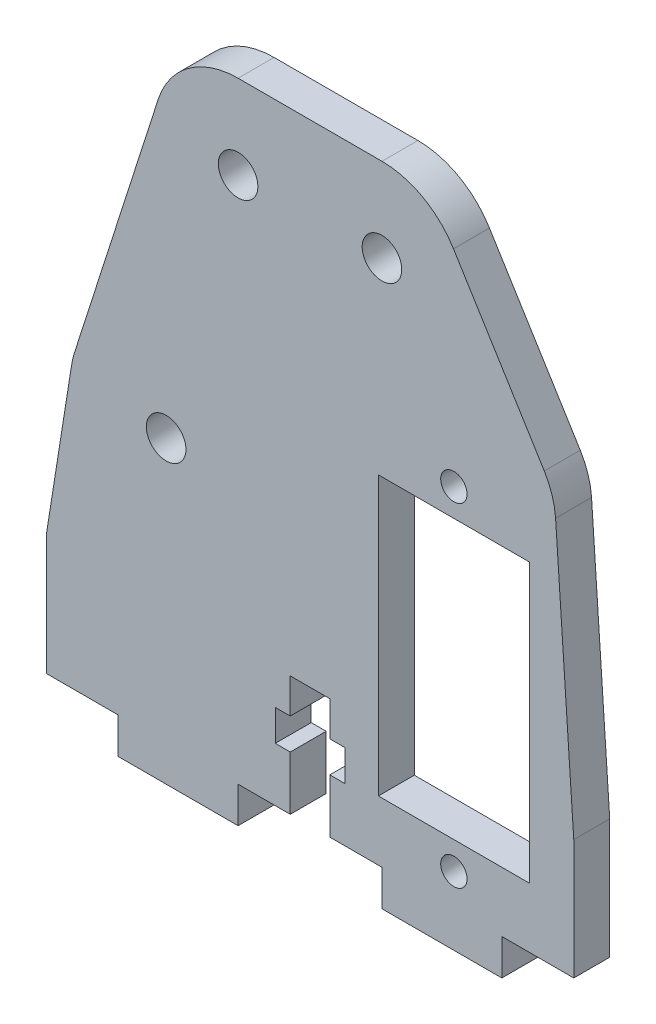
SolidWorks part; units mm, degrees
ref_plane "Спереди" through (0, 0, 0) normal (0, 0, 1) x (1, 0, 0)
ref_plane "Сверху" through (0, 0, 0) normal (0, 1, 0) x (1, 0, 0)
ref_plane "Справа" through (0, 0, 0) normal (1, 0, 0) x (0, 0, -1)
other "Configuration Table"
sketch "Eskiz_kontur" plane through (0, 0, 0) normal (0, 0, 1) x (1, 0, 0)
  line L0 (-19.6085, 2.4721) -> (-12.6574, 24.1631)
  line L1 (-6, 29) -> (6, 29)
  line L2 (-22, -12) -> (-19.9015, 1.2515)
  line L3 (-22, -22) -> (-22, -12)
  line L4 (11.9685, 25.6575) -> (19.5422, 13.3962)
  line L5 (-16, -22) -> (-22, -22)
  line L6 (-16, -25) -> (-16, -22)
  line L7 (20.4842, 10.4534) -> (22, -12)
  line L8 (-6, -25) -> (-16, -25)
  line L9 (22, -12) -> (22, -22)
  line L10 (-6, -22) -> (-6, -25)
  line L11 (22, -22) -> (16, -22)
  line L12 (-1.65, -22) -> (-6, -22)
  line L13 (16, -22) -> (16, -25)
  line L14 (-1.65, -17.5) -> (-1.65, -22)
  line L15 (16, -25) -> (6, -25)
  line L16 (-2.9, -17.5) -> (-1.65, -17.5)
  line L17 (6, -25) -> (6, -22)
  line L18 (-2.9, -14.9) -> (-2.9, -17.5)
  line L19 (6, -22) -> (1.65, -22)
  line L20 (-1.65, -14.9) -> (-2.9, -14.9)
  line L21 (1.65, -22) -> (1.65, -17.5)
  line L22 (-1.65, -12) -> (-1.65, -14.9)
  line L23 (1.65, -17.5) -> (2.9, -17.5)
  line L24 (1.65, -12) -> (-1.65, -12)
  line L25 (2.9, -17.5) -> (2.9, -14.9)
  line L26 (1.65, -14.9) -> (1.65, -12)
  line L27 (2.9, -14.9) -> (1.65, -14.9)
  line L28 (18.3, 6.2) -> (5.7, 6.2)
  line L29 (5.7, 6.2) -> (5.7, -17)
  line L30 (18.3, -17) -> (18.3, 6.2)
  line L31 (5.7, -17) -> (18.3, -17)
  arc A0 (-12.6574, 24.1631) -> (-6, 29) centre (-6, 22) cw
  arc A1 (-19.9015, 1.2515) -> (-19.6085, 2.4721) centre (-11.9999, 0) cw
  arc A2 (6, 29) -> (11.9685, 25.6575) centre (6, 22) cw
  arc A3 (19.5422, 13.3962) -> (20.4842, 10.4534) centre (14, 10) cw
extrude "Plastina" add sketch "Eskiz_kontur" along normal blind 3
sketch "Eskiz_otverstiya" plane through (0, 0, 0) normal (0, 0, 1) x (1, 0, 0)
  circle A0 centre (-12, 0) radius 1.65
  circle A1 centre (12, -19.3) radius 1.1
  circle A2 centre (-6, 22) radius 1.65
  circle A3 centre (12, 8.5) radius 1.1
  circle A4 centre (6, 22) radius 1.65
  dimension "d1" = 3.3
  dimension "d2" = 2.2
  dimension "d3" = 3.3
  dimension "d4" = 2.2
  dimension "d5" = 3.3
extrude "Otverstiya" cut sketch "Eskiz_otverstiya" against normal through all and the other way through all
equation "\"T3\" = 3"
equation "\"T5\" = 5"
equation "\"D_M3\" = 3.3"
equation "\"D_M2\" = 2.2"
equation "\"D_M3_TAP\" = 2.5"
equation "\"D_M4\" = 4.5"
equation "\"L1\" = 100"
equation "\"L2\" = 100"
equation "\"D1@Plastina\" = \"T3\""
equation "\"d1@Eskiz_otverstiya\" = \"D_M3\""
equation "\"d2@Eskiz_otverstiya\" = \"D_M2\""
equation "\"d3@Eskiz_otverstiya\" = \"D_M3\""
equation "\"d4@Eskiz_otverstiya\" = \"D_M2\""
equation "\"d5@Eskiz_otverstiya\" = \"D_M3\""
